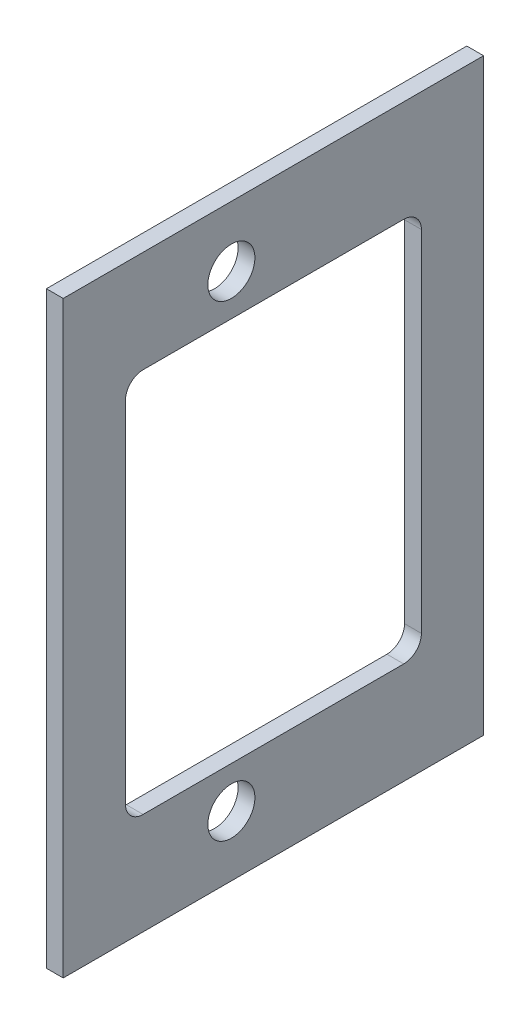
SolidWorks part; units mm, degrees
ref_plane "Front Plane" through (0, 0, 0) normal (0, 0, 1) x (1, 0, 0)
ref_plane "Top Plane" through (0, 0, 0) normal (0, 1, 0) x (1, 0, 0)
ref_plane "Right Plane" through (0, 0, 0) normal (1, 0, 0) x (0, 0, -1)
sketch "Sketch1" plane through (0, 0, 0) normal (1, 0, 0) x (0, 0, -1)
  line L1 (12.5, -17.5) -> (-12.5, -17.5)
  line L2 (12.5, -17.5) -> (12.5, 17.5)
  line L3 (12.5, 17.5) -> (-12.5, 17.5)
  line L4 (-12.5, -17.5) -> (-12.5, 17.5)
  line L5 (12.5, -17.5) -> (-12.5, 17.5) construction
  line L6 (12.5, 17.5) -> (-12.5, -17.5) construction
  point P0 (0, 0)
  dimension "D1" = 25
  dimension "D2" = 35
extrude "Boss-Extrude1" add sketch "Sketch1" along normal blind 1
sketch "Sketch2" plane through (0, 0, 0) normal (-1, 0, 0) x (0, 0, 1)
  line L0 (-8.8, 10.4) -> (-8.8, -10.4) construction
  line L1 (-7.75, 11.45) -> (7.75, 11.45) construction
  line L2 (8.8, 10.4) -> (8.8, -10.4) construction
  line L3 (7.75, -11.45) -> (-7.75, -11.45) construction
  line L4 (-8.8, 10.4) -> (-8.8, -10.4)
  line L5 (-7.75, 11.45) -> (7.75, 11.45)
  line L6 (8.8, 10.4) -> (8.8, -10.4)
  line L7 (7.75, -11.45) -> (-7.75, -11.45)
  arc A2 (-8.8, -10.4) -> (-7.75, -11.45) centre (-7.75, -10.4) ccw construction
  arc A3 (-7.75, 11.45) -> (-8.8, 10.4) centre (-7.75, 10.4) ccw construction
  arc A4 (8.8, 10.4) -> (7.75, 11.45) centre (7.75, 10.4) ccw construction
  arc A5 (7.75, -11.45) -> (8.8, -10.4) centre (7.75, -10.4) ccw construction
  arc A8 (-8.8, -10.4) -> (-7.75, -11.45) centre (-7.75, -10.4) ccw
  arc A9 (-7.75, 11.45) -> (-8.8, 10.4) centre (-7.75, 10.4) ccw
  arc A10 (8.8, 10.4) -> (7.75, 11.45) centre (7.75, 10.4) ccw
  arc A11 (7.75, -11.45) -> (8.8, -10.4) centre (7.75, -10.4) ccw
  circle A12 centre (2.5, 13.9) radius 1.4 construction
  circle A13 centre (2.5, -13.9) radius 1.4 construction
  circle A14 centre (2.5, 13.9) radius 1.4
  circle A15 centre (2.5, -13.9) radius 1.4
extrude "Cut-Extrude1" cut sketch "Sketch2" against normal up to surface (1 mm away) up to face at (1, 0, 0)
